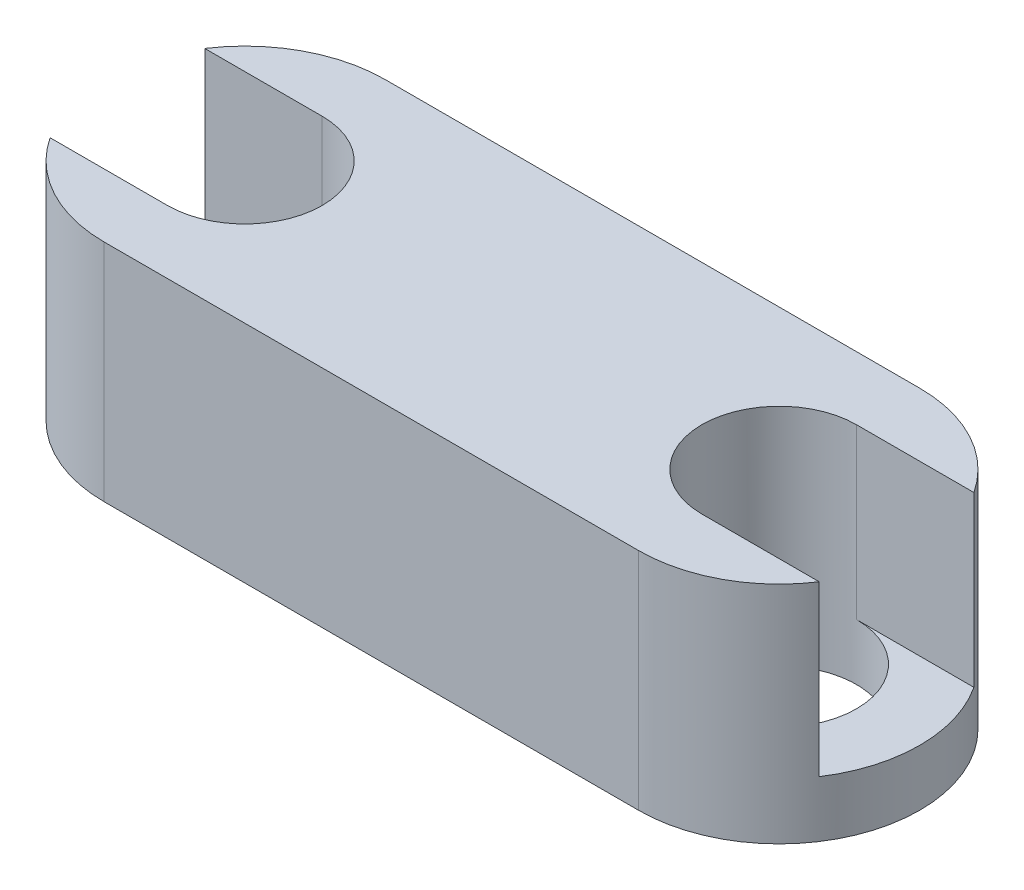
SolidWorks part; units mm, degrees
ref_plane "Front Plane" through (0, 0, 0) normal (0, 0, 1) x (1, 0, 0)
ref_plane "Top Plane" through (0, 0, 0) normal (0, 1, 0) x (1, 0, 0)
ref_plane "Right Plane" through (0, 0, 0) normal (1, 0, 0) x (0, 0, -1)
sketch "Sketch1" plane through (0, 0, 0) normal (0, 1, 0) x (1, 0, 0)
  line L0 (-7.7125, 6.5) -> (11.2875, 6.5)
  line L1 (-7.7125, -3.5) -> (11.2875, -3.5)
  arc A0 (-7.7125, 6.5) -> (-7.7125, -3.5) centre (-7.7125, 1.5) ccw
  arc A1 (11.2875, -3.5) -> (11.2875, 6.5) centre (11.2875, 1.5) ccw
  circle A2 centre (-7.7125, 1.5) radius 2.75
  circle A3 centre (11.2875, 1.5) radius 2.75
  dimension "D3" = 5.5
  dimension "D4" = 5.5
  dimension "D5" = 5
  dimension "D2" = 19
extrude "Boss-Extrude1" add sketch "Sketch1" along normal blind 8
sketch "Sketch2" plane through (0, 8, 0) normal (0, 1, 0) x (1, 0, 0)
  line L0 (1.7875, 6.5) -> (1.7875, -6.8516) construction
  line L1 (-7.7125, 4.25) -> (-17.5586, 4.25)
  line L2 (-7.7125, 4.25) -> (-7.7125, -1.25)
  line L3 (-7.7125, -1.25) -> (-17.5586, -1.25)
  line L4 (-17.5586, 4.25) -> (-17.5586, -1.25)
  line L5 (11.2875, 6.5) -> (-7.7125, 6.5) construction
  line L6 (11.2875, -1.25) -> (21.1335, -1.25)
  line L7 (21.1335, 4.25) -> (21.1335, -1.25)
  line L8 (11.2875, 4.25) -> (21.1335, 4.25)
  line L9 (11.2875, 4.25) -> (11.2875, -1.25)
  circle A0 centre (-7.7125, 1.5) radius 2.75 construction
  dimension "D1" = 5.5
extrude "Cut-Extrude1" cut sketch "Sketch2" against normal blind 6
